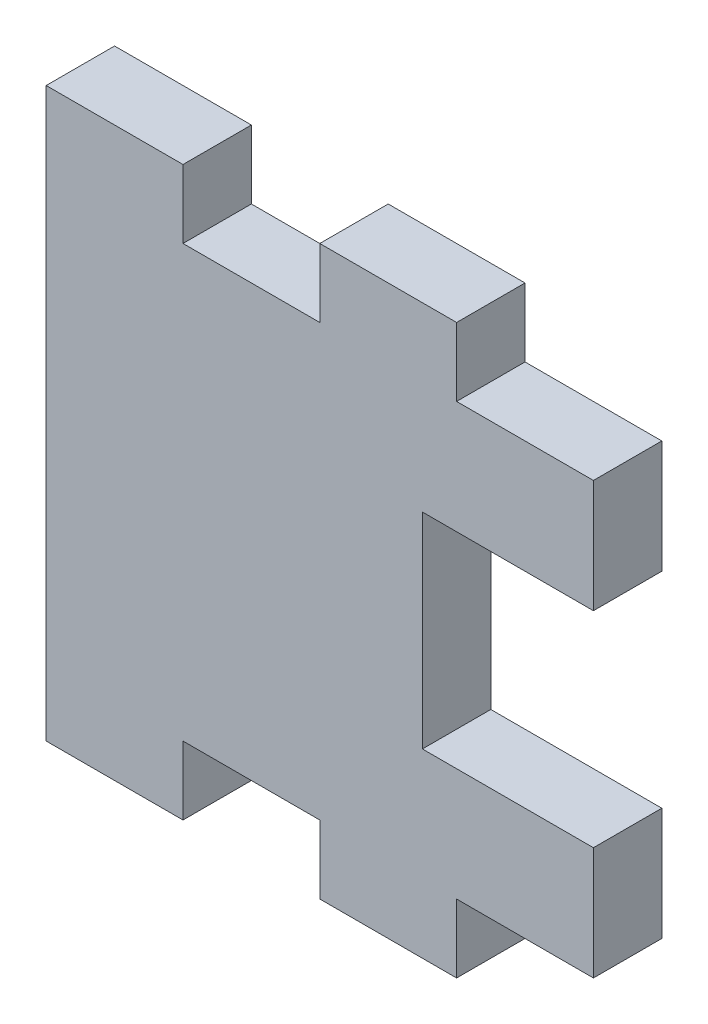
SolidWorks part; units mm, degrees
material "Acrylic (Medium-high impact)"
ref_plane "Front Plane" through (0, 0, 0) normal (0, 0, 1) x (1, 0, 0)
ref_plane "Top Plane" through (0, 0, 0) normal (0, 1, 0) x (1, 0, 0)
ref_plane "Right Plane" through (0, 0, 0) normal (1, 0, 0) x (0, 0, -1)
sketch "Sketch1" plane through (0, 0, 0) normal (0, 0, 1) x (1, 0, 0)
  line L0 (0, 0) -> (0, -3.175)
  line L1 (6.35, 0) -> (12.7, 0)
  line L2 (0, 0) -> (0, 10)
  line L3 (6.35, 20) -> (12.7, 20)
  line L4 (25.4, 0) -> (25.4, 5.2375)
  line L5 (0, -3.175) -> (6.35, -3.175)
  line L6 (6.35, -3.175) -> (6.35, 0)
  line L7 (12.7, 0) -> (12.7, -3.175)
  line L8 (12.7, -3.175) -> (19.05, -3.175)
  line L9 (19.05, -3.175) -> (19.05, 0)
  line L10 (19.05, 0) -> (25.4, 0)
  line L11 (0, 10) -> (25.4, 10) construction
  line L12 (19.05, 23.175) -> (19.05, 20)
  line L13 (12.7, 23.175) -> (19.05, 23.175)
  line L14 (12.7, 20) -> (12.7, 23.175)
  line L15 (6.35, 23.175) -> (6.35, 20)
  line L16 (0, 23.175) -> (6.35, 23.175)
  line L17 (0, 20) -> (0, 23.175)
  line L18 (19.05, 20) -> (25.4, 20)
  line L19 (25.4, 5.2375) -> (17.4625, 5.2375)
  line L20 (25.4, 14.7625) -> (25.4, 20)
  line L22 (0, 10) -> (0, 20)
  line L23 (25.4, 14.7625) -> (17.4625, 14.7625)
  line L24 (17.4625, 14.7625) -> (17.4625, 5.2375)
  point P22 (17.4625, 10)
  dimension "D1" = 6.35
  dimension "D2" = 3.175
  dimension "D3" = 20
  dimension "D4" = 4.7625
  dimension "D6" = 7.9375
extrude "Boss-Extrude1" add sketch "Sketch1" along normal blind 3.175
